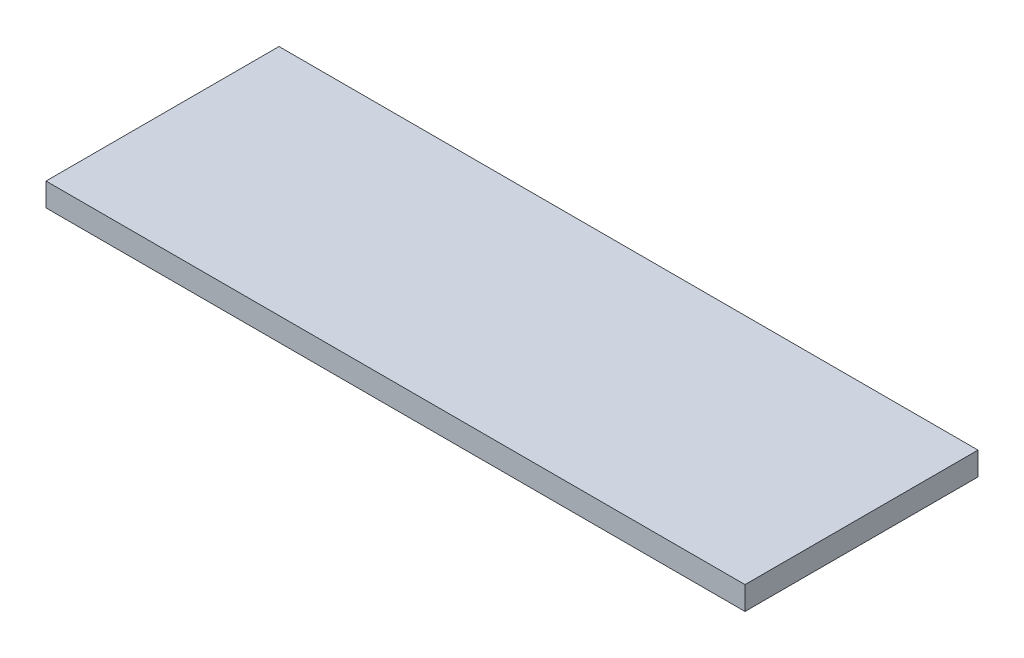
SolidWorks part; units mm, degrees
ref_plane "Plano frontal" through (0, 0, 0) normal (0, 0, 1) x (1, 0, 0)
ref_plane "Plano superior" through (0, 0, 0) normal (0, 1, 0) x (1, 0, 0)
ref_plane "Plano direito" through (0, 0, 0) normal (1, 0, 0) x (0, 0, -1)
sketch "Esboço2" plane through (0, 0, 0) normal (0, 1, 0) x (1, 0, 0)
  line L1 (0, 0) -> (30, 0)
  line L2 (0, 0) -> (0, 10)
  line L3 (0, 10) -> (30, 10)
  line L4 (30, 0) -> (30, 10)
extrude "Ressalto-extrusão1" add sketch "Esboço2" along normal blind 1
